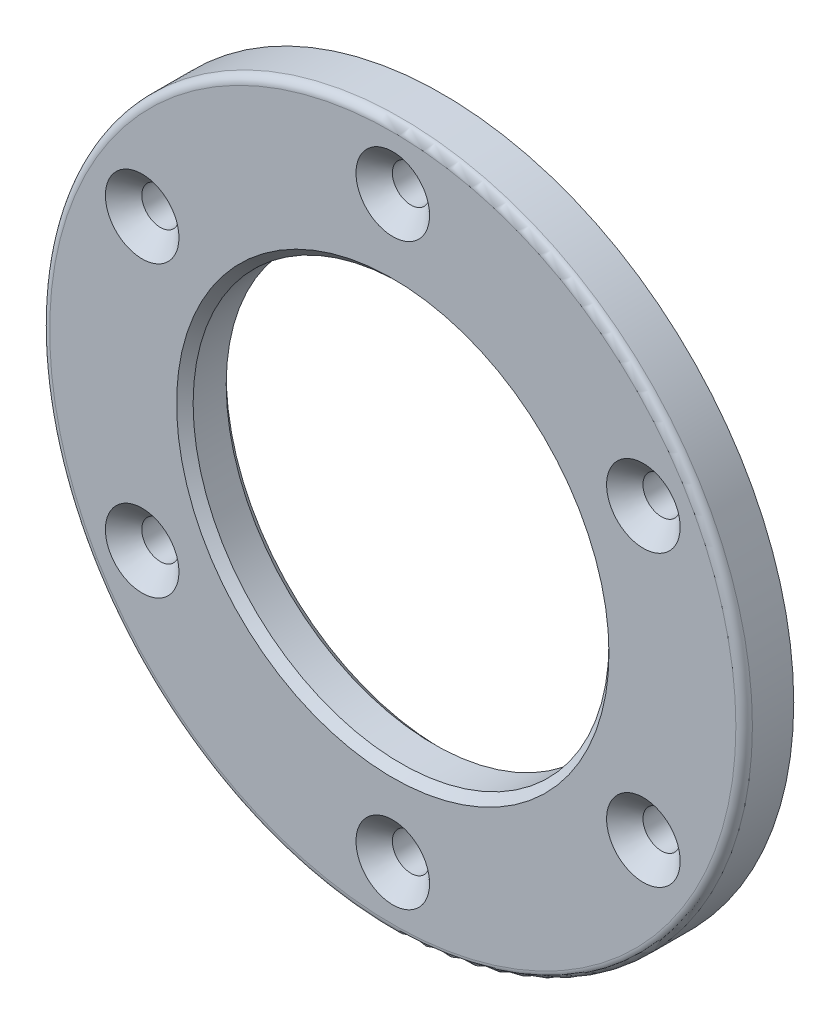
SolidWorks part; units mm, degrees
ref_plane "Front Plane" through (0, 0, 0) normal (0, 0, 1) x (1, 0, 0)
ref_plane "Top Plane" through (0, 0, 0) normal (0, 1, 0) x (1, 0, 0)
ref_plane "Right Plane" through (0, 0, 0) normal (1, 0, 0) x (0, 0, -1)
sketch "Sketch1" plane through (0, 0, 0) normal (0, 0, 1) x (1, 0, 0)
  circle A0 centre (0, 0) radius 42.5
  dimension "D1" = 85
extrude "Boss-Extrude1" add sketch "Sketch1" along normal blind 6
sketch "Sketch2" plane through (0, 0, 6) normal (0, 0, 1) x (1, 0, 0)
  circle A0 centre (0, 0) radius 25.15
  dimension "D1" = 50.3
extrude "Cut-Extrude1" cut sketch "Sketch2" against normal through all
sketch "Sketch3" plane through (0, 0, 6) normal (0, 0, 1) x (1, 0, 0)
  line L0 (0, 0) -> (0, 42.5) construction
  circle A0 centre (0, 0) radius 42.5 construction
  circle A1 centre (0, 35) radius 2.25
  dimension "D1" = 4.5
  dimension "D2" = 35
extrude "Cut-Extrude2" cut sketch "Sketch3" against normal through all
chamfer "Chamfer2" distance 2.2 angle 45 1 edges at (2.25, 35, 6)
pattern_circular "CirPattern1" count 6 over 360 about axis through (0, 0, 0) along (0, 0, 1) of "Cut-Extrude2", "Chamfer2"
chamfer "Chamfer1" distance 1 angle 45 2 edges at (25.15, 0, 0) (25.15, 0, 6)
fillet "Fillet1" radius 1 1 edges at (42.5, 0, 6)
